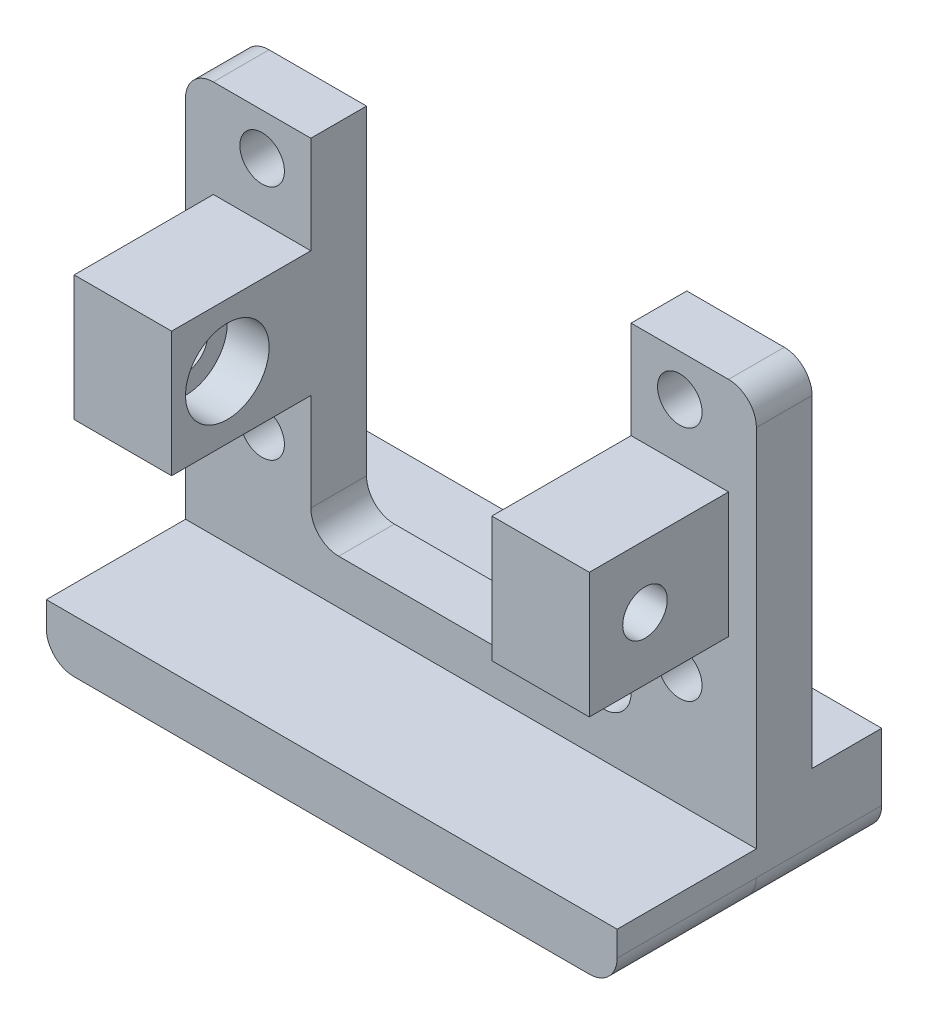
SolidWorks part; units mm, degrees
material "ABS"
ref_plane "前视基准面" through (0, 0, 0) normal (0, 0, 1) x (1, 0, 0)
ref_plane "上视基准面" through (0, 0, 0) normal (0, 1, 0) x (1, 0, 0)
ref_plane "右视基准面" through (0, 0, 0) normal (1, 0, 0) x (0, 0, -1)
sketch "草图1" plane through (0, 0, 0) normal (0, 0, 1) x (1, 0, 0)
  line L1 (-11.5, -13.5) -> (-11.5, 11.5)
  line L2 (-11.5, 11.5) -> (-18.5, 11.5)
  line L3 (11.5, 11.5) -> (11.5, -13.5)
  line L6 (17, 11.5) -> (-17, 11.5) construction
  line L13 (11.5, 11.5) -> (18.5, 11.5)
  line L14 (20.5, 9.5) -> (20.5, -18.5)
  line L15 (18.5, -20.5) -> (-18.5, -20.5)
  line L19 (-20.5, 9.5) -> (-20.5, -18.5)
  line L20 (-11.5, -13.5) -> (11.5, -13.5)
  circle A14 centre (-15, 8.5) radius 1.6
  circle A15 centre (-15, -8.5) radius 1.6
  arc A20 (-20.5, -18.5) -> (-18.5, -20.5) centre (-18.5, -18.5) ccw
  arc A23 (-18.5, 11.5) -> (-20.5, 9.5) centre (-18.5, 9.5) ccw
  circle A24 centre (15, 8.5) radius 1.6
  circle A25 centre (15, -8.5) radius 1.6
  arc A26 (18.5, 11.5) -> (20.5, 9.5) centre (18.5, 9.5) cw
  arc A27 (20.5, -18.5) -> (18.5, -20.5) centre (18.5, -18.5) cw
  dimension "D2" = 28
  dimension "D3" = 2
  dimension "D1" = 23
  dimension "D4" = 2
  dimension "D5" = 2
  dimension "D8" = 2
  dimension "D9" = 25
  dimension "D6" = 7
  dimension "D7" = 7
extrude "凸台-拉伸5" add sketch "草图1" along normal blind 3 and the other way up to surface (1 mm away)
sketch "草图6" plane through (0, 0, 3) normal (0, 0, 1) x (1, 0, 0)
  line L0 (11.5, 11.5) -> (11.5, -13.5) construction
  line L1 (-11.5, 4.5) -> (-18.5, 4.5)
  line L2 (-11.5, 4.5) -> (-11.5, -4.5)
  line L3 (-11.5, -4.5) -> (-18.5, -4.5)
  line L4 (-18.5, 4.5) -> (-18.5, -4.5)
  line L5 (11.5, 4.5) -> (18.5, 4.5)
  line L7 (-11.5, 11.5) -> (-18.5, 11.5) construction
  line L8 (-11.5, -13.5) -> (-11.5, 11.5) construction
  line L9 (11.5, 4.5) -> (11.5, -4.5)
  line L10 (11.5, -4.5) -> (18.5, -4.5)
  line L11 (18.5, 4.5) -> (18.5, -4.5)
  dimension "D1" = 9
  dimension "D2" = 7
  dimension "D3" = 7
  dimension "D4" = 0
extrude "凸台-拉伸6" add sketch "草图6" along normal blind 10
sketch "草图7" plane through (-20.5, 0, 0) normal (-1, 0, 0) x (0, 0, 1)
  line L0 (13, 4.5) -> (13, -4.5) construction
  circle A0 centre (9, 0) radius 1.6
  dimension "D1" = 4
extrude "切除-拉伸3" cut sketch "草图7" against normal through all both and the other way through all
fillet "圆角1" radius 2 2 edges at (-11.5, -13.5, 1) (11.5, -13.5, 1)
sketch "草图8" plane through (0, 0, -1) normal (0, 0, -1) x (-1, 0, 0)
  line L0 (-20.5, -18.5) -> (-20.5, -13.7)
  line L1 (-20.5, -18.5) -> (-20.5, 9.5) construction
  line L2 (-20.5, -13.7) -> (20.5, -13.7)
  line L3 (20.5, 9.5) -> (20.5, -18.5) construction
  line L4 (20.5, -13.7) -> (20.5, -18.5)
  line L8 (18.5, 11.5) -> (11.5, 11.5)
  line L9 (11.5, 11.5) -> (11.5, -11.5)
  line L10 (9.5, -13.5) -> (-9.5, -13.5)
  line L11 (-11.5, -11.5) -> (-11.5, 11.5)
  line L12 (-11.5, 11.5) -> (-18.5, 11.5)
  line L13 (-20.5, 9.5) -> (-20.5, -18.5)
  line L14 (-18.5, -20.5) -> (18.5, -20.5)
  line L15 (20.5, -18.5) -> (20.5, 9.5)
  line L22 (-18.5, -20.5) -> (18.5, -20.5)
  arc A6 (9.5, -13.5) -> (11.5, -11.5) centre (9.5, -11.5) ccw
  arc A7 (-11.5, -11.5) -> (-9.5, -13.5) centre (-9.5, -11.5) ccw
  arc A8 (-18.5, 11.5) -> (-20.5, 9.5) centre (-18.5, 9.5) ccw
  arc A9 (-20.5, -18.5) -> (-18.5, -20.5) centre (-18.5, -18.5) ccw
  arc A10 (18.5, -20.5) -> (20.5, -18.5) centre (18.5, -18.5) ccw
  arc A11 (20.5, 9.5) -> (18.5, 11.5) centre (18.5, 9.5) ccw
  arc A15 (-20.5, -18.5) -> (-18.5, -20.5) centre (-18.5, -18.5) ccw
  arc A16 (18.5, -20.5) -> (20.5, -18.5) centre (18.5, -18.5) ccw
  dimension "D1" = 0
  dimension "D2" = 4.8
extrude "凸台-拉伸7" add sketch "草图8" along normal up to surface (5 mm away)
sketch "草图9" plane through (11.5, 0, 0) normal (-1, 0, 0) x (0, 0, 1)
  circle A0 centre (9, 0) radius 3
extrude "切除-拉伸4" cut sketch "草图9" against normal blind 3
sketch "草图10" plane through (-11.5, 0, 0) normal (1, 0, 0) x (0, 0, -1)
  circle A0 centre (-9, 0) radius 3
extrude "切除-拉伸5" cut sketch "草图10" against normal blind 3
sketch "草图11" plane through (0, 0, 3) normal (0, 0, 1) x (1, 0, 0)
  line L1 (-20.5, -16.7) -> (20.5, -16.7)
  line L2 (-20.5, -16.7) -> (-20.5, -20.5)
  line L3 (-20.5, -20.5) -> (20.5, -20.5)
  line L4 (20.5, -16.7) -> (20.5, -20.5)
extrude "凸台-拉伸8" add sketch "草图11" along normal blind 10
fillet "圆角2" radius 2 2 edges at (-20.5, -20.5, 8) (20.5, -20.5, 8)
